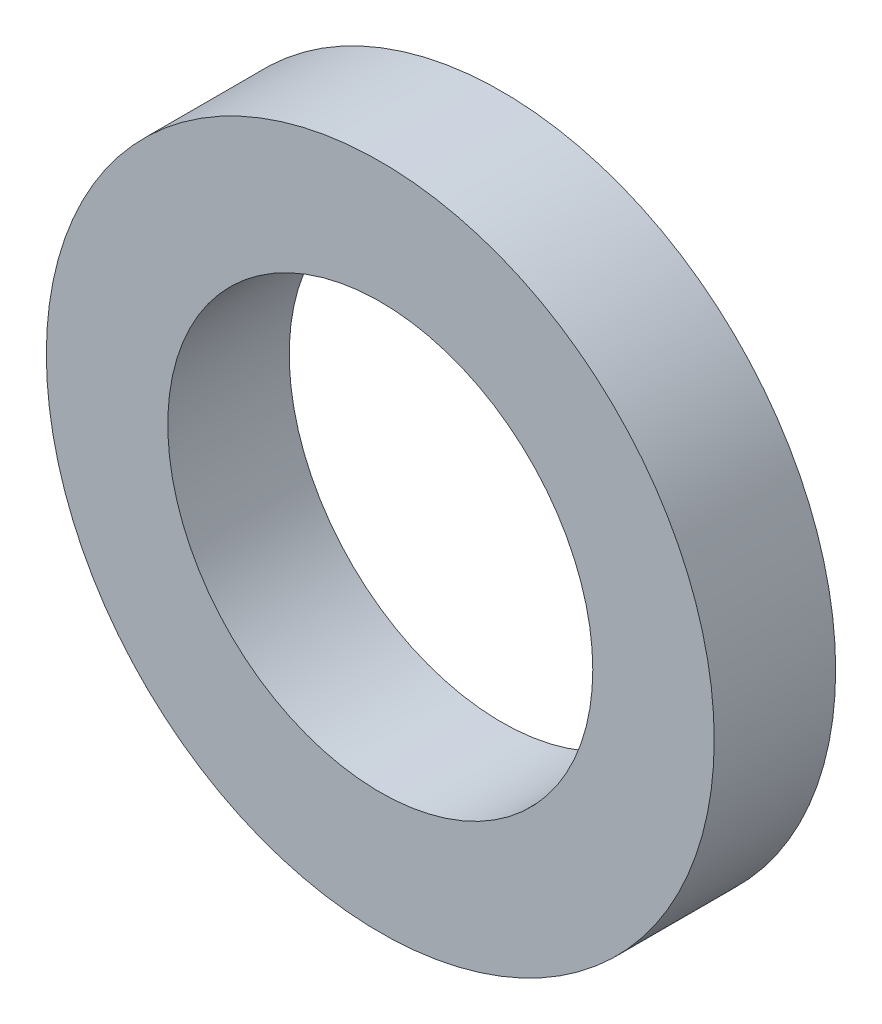
SolidWorks part; units mm, degrees
ref_plane "Front Plane" through (0, 0, 0) normal (0, 0, 1) x (1, 0, 0)
ref_plane "Top Plane" through (0, 0, 0) normal (0, 1, 0) x (1, 0, 0)
ref_plane "Right Plane" through (0, 0, 0) normal (1, 0, 0) x (0, 0, -1)
sketch "Sketch1" plane through (0, 0, 0) normal (0, 0, 1) x (1, 0, 0)
  circle A0 centre (0, 0) radius 22.225
  circle A1 centre (0, 0) radius 34.925
  dimension "D1" = 12.7
  dimension "D2" = 44.45
extrude "Boss-Extrude1" add sketch "Sketch1" along normal blind 12.7
